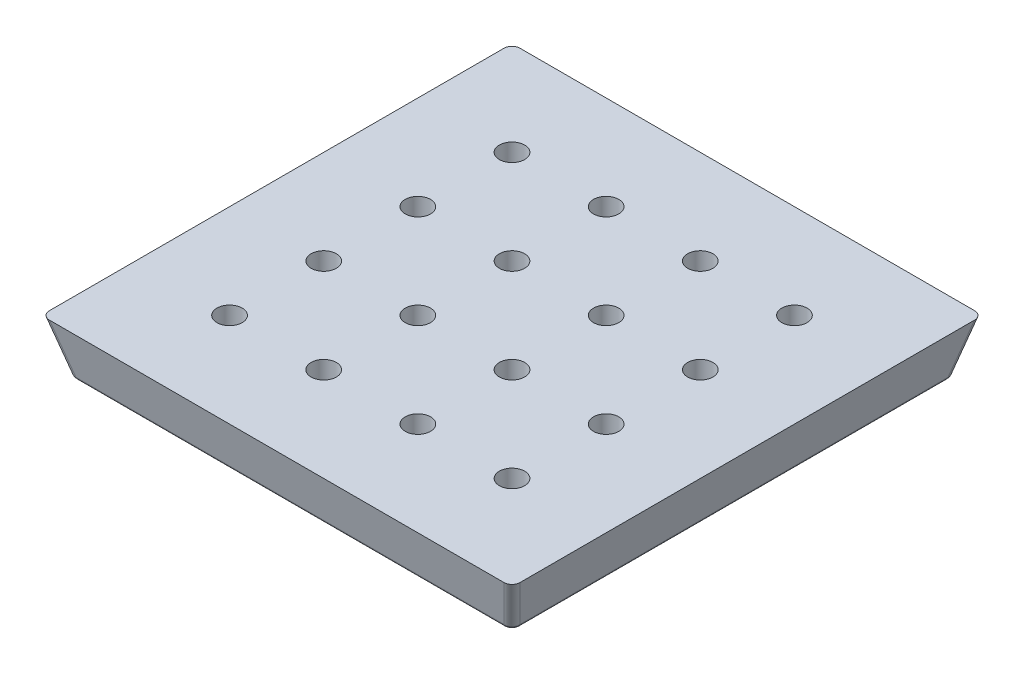
SolidWorks part; units mm, degrees
ref_plane "Front" through (0, 0, 0) normal (0, 0, 1) x (1, 0, 0)
ref_plane "Top" through (0, 0, 0) normal (0, 1, 0) x (1, 0, 0)
ref_plane "Right" through (0, 0, 0) normal (1, 0, 0) x (0, 0, -1)
sketch "Sketch1" plane through (0, 0, 0) normal (0, 1, 0) x (1, 0, 0)
  line L0 (0, 0) -> (266.7, 0)
  line L1 (266.7, 0) -> (266.7, 266.7)
  line L2 (266.7, 266.7) -> (0, 266.7)
  line L3 (0, 266.7) -> (0, 0)
extrude "Boss-Extrude1" add sketch "Sketch1" along normal blind 31.75 draft 15 draft outward yes
sketch "Sketch3" plane through (0, 31.75, 0) normal (0, 1, 0) x (1, 0, 0)
  line L0 (-8.5074, -8.5074) -> (-8.5074, 48.2362)
  line L1 (-8.5074, -8.5074) -> (275.2074, -8.5074) construction
  line L2 (-8.5074, 275.2074) -> (-8.5074, -8.5074) construction
  line L3 (-8.5074, 48.2362) -> (48.2362, 48.2362)
  circle A0 centre (48.2362, 48.2362) radius 3.048
  circle A1 centre (104.9798, 48.2362) radius 3.048
  circle A2 centre (161.7234, 48.2362) radius 3.048
  circle A3 centre (218.467, 48.2362) radius 3.048
  circle A4 centre (104.9798, 104.9798) radius 3.048
  circle A5 centre (161.7234, 104.9798) radius 3.048
  circle A6 centre (218.467, 104.9798) radius 3.048
  circle A7 centre (104.9798, 161.7234) radius 3.048
  circle A8 centre (161.7234, 161.7234) radius 3.048
  circle A9 centre (218.467, 161.7234) radius 3.048
  circle A10 centre (104.9798, 218.467) radius 3.048
  circle A11 centre (161.7234, 218.467) radius 3.048
  circle A12 centre (218.467, 218.467) radius 3.048
  circle A13 centre (48.2362, 104.9798) radius 3.048
  circle A14 centre (48.2362, 161.7234) radius 3.048
  circle A15 centre (48.2362, 218.467) radius 3.048
  dimension "D1" = 4
  dimension "D2" = 4
extrude "Cut-Extrude1" cut sketch "Sketch3" against normal blind 31.75
sketch "Sketch4" plane through (0, 31.75, 0) normal (0, 1, 0) x (1, 0, 0)
  circle A0 centre (218.467, 48.2362) radius 7.62
  circle A1 centre (161.7234, 48.2362) radius 7.62
  circle A2 centre (104.9798, 48.2362) radius 7.62
  circle A3 centre (48.2362, 48.2362) radius 7.62
  circle A4 centre (161.7234, 104.9798) radius 7.62
  circle A5 centre (104.9798, 104.9798) radius 7.62
  circle A6 centre (48.2362, 104.9798) radius 7.62
  circle A7 centre (161.7234, 161.7234) radius 7.62
  circle A8 centre (104.9798, 161.7234) radius 7.62
  circle A9 centre (48.2362, 161.7234) radius 7.62
  circle A10 centre (161.7234, 218.467) radius 7.62
  circle A11 centre (104.9798, 218.467) radius 7.62
  circle A12 centre (48.2362, 218.467) radius 7.62
  circle A13 centre (218.467, 104.9798) radius 7.62
  circle A14 centre (218.467, 161.7234) radius 7.62
  circle A15 centre (218.467, 218.467) radius 7.62
  dimension "D1" = 4
  dimension "D2" = 4
extrude "Cut-Extrude2" cut sketch "Sketch4" against normal blind 12.7
fillet "Fillet1" radius 5.08 4 edges at (-4.2537, 15.875, -270.9537) (270.9537, 15.875, -270.9537) (270.9537, 15.875, 4.2537) (-4.2537, 15.875, 4.2537)
fillet "Fillet2" radius 2.54 8 edges at (1.4178, 0, -265.2822) (133.35, 0, -266.7) (265.2822, 0, -265.2822) (266.7, 0, -133.35) (265.2822, 0, -1.4178) (133.35, 0, 0) (1.4178, 0, -1.4178) (0, 0, -133.35)
